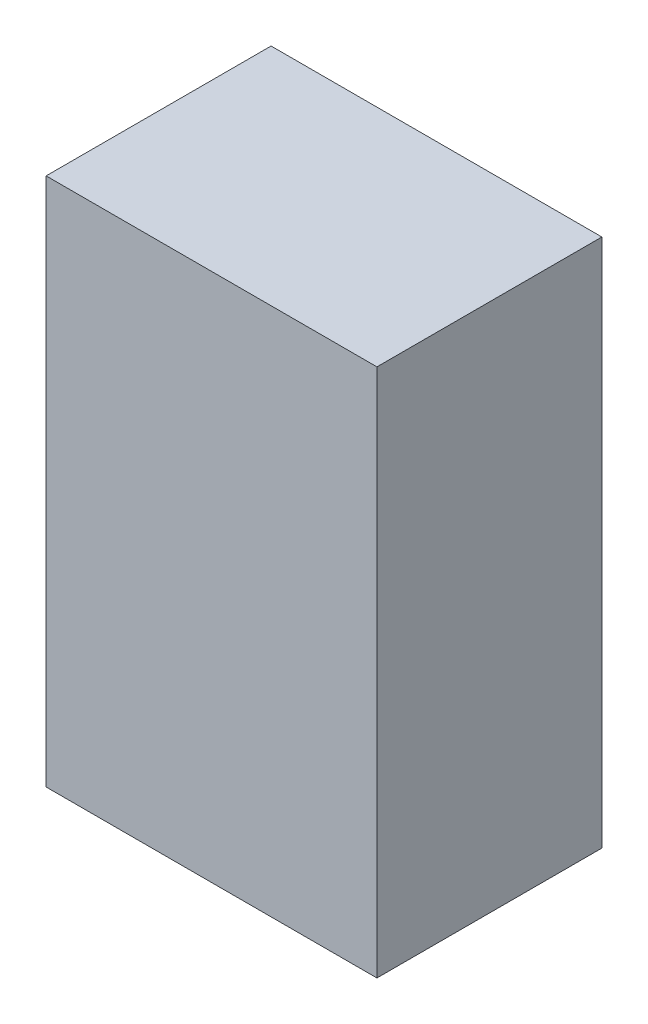
SolidWorks part; units mm, degrees
ref_plane "Front Plane" through (0, 0, 0) normal (0, 0, 1) x (1, 0, 0)
ref_plane "Top Plane" through (0, 0, 0) normal (0, 1, 0) x (1, 0, 0)
ref_plane "Right Plane" through (0, 0, 0) normal (1, 0, 0) x (0, 0, -1)
sketch "Sketch1" plane through (0, 0, 0) normal (0, 1, 0) x (1, 0, 0)
  line L1 (-158.75, 107.95) -> (158.75, 107.95)
  line L2 (-158.75, 107.95) -> (-158.75, -107.95)
  line L3 (-158.75, -107.95) -> (158.75, -107.95)
  line L4 (158.75, 107.95) -> (158.75, -107.95)
  line L5 (-158.75, 107.95) -> (158.75, -107.95) construction
  line L6 (-158.75, -107.95) -> (158.75, 107.95) construction
  point P0 (0, 0)
  dimension "D1" = 317.5
  dimension "D2" = 215.9
extrude "Boss-Extrude1" add sketch "Sketch1" along normal blind 508
